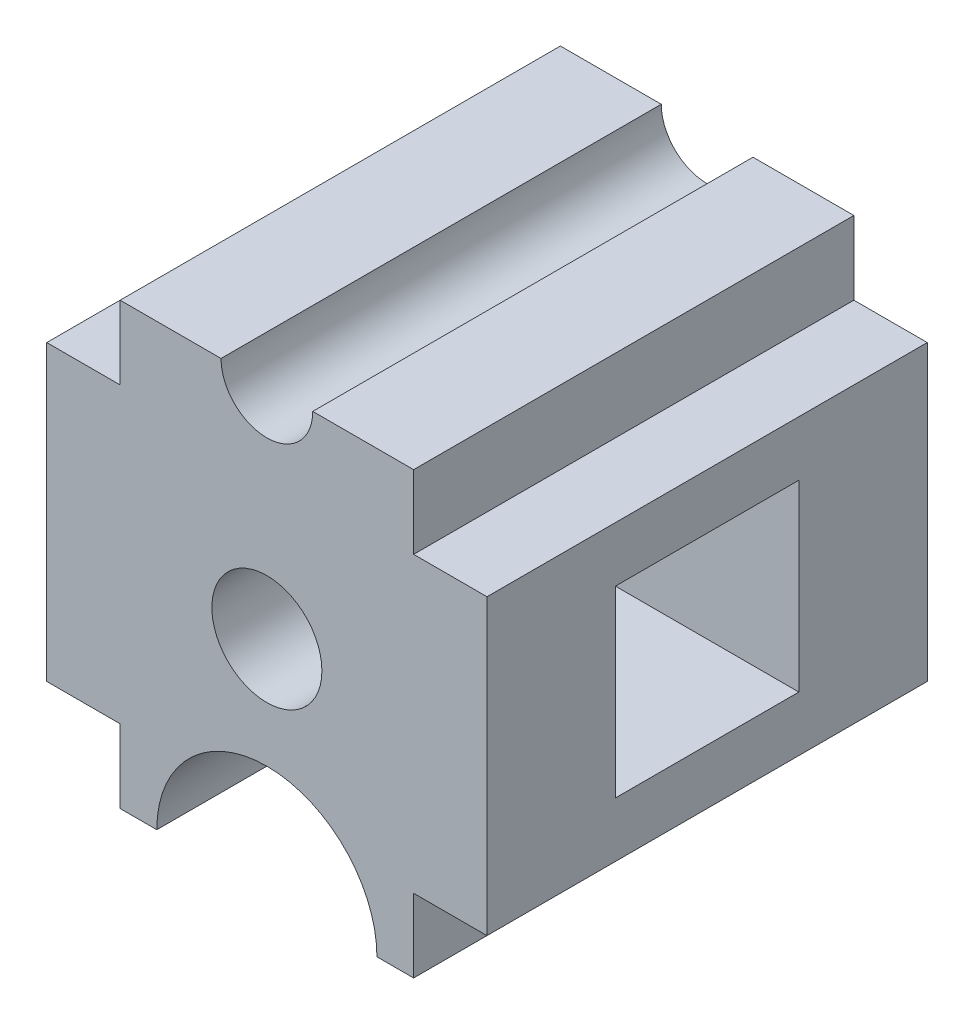
SolidWorks part; units mm, degrees
ref_plane "Front Plane" through (0, 0, 0) normal (0, 0, 1) x (1, 0, 0)
ref_plane "Top Plane" through (0, 0, 0) normal (0, 1, 0) x (1, 0, 0)
ref_plane "Right Plane" through (0, 0, 0) normal (1, 0, 0) x (0, 0, -1)
sketch "Sketch1" plane through (0, 0, 0) normal (0, 0, 1) x (1, 0, 0)
  line L1 (-60, 60) -> (60, 60)
  line L2 (-60, 60) -> (-60, -60)
  line L3 (-60, -60) -> (60, -60)
  line L4 (60, 60) -> (60, -60)
  line L5 (-60, 60) -> (60, -60) construction
  line L6 (-60, -60) -> (60, 60) construction
  point P0 (0, 0)
  dimension "D1" = 120
  dimension "D2" = 120
extrude "Boss-Extrude1" add sketch "Sketch1" along normal blind 120
sketch "Sketch2" plane through (0, 0, 120) normal (0, 0, 1) x (1, 0, 0)
  line L0 (-60, -60) -> (60, -60) construction
  line L1 (60, -60) -> (40, -60)
  line L2 (40, -60) -> (40, -40)
  line L3 (40, -40) -> (60, -40)
  line L4 (60, -60) -> (60, 60) construction
  line L5 (0, -60) -> (0, 60) construction
  line L6 (60, 60) -> (-60, 60) construction
  line L7 (60, -40) -> (60, -60)
  line L8 (-60, -40) -> (-60, -60)
  line L9 (-60, -60) -> (-40, -60)
  line L10 (-40, -60) -> (-40, -40)
  line L11 (-40, -40) -> (-60, -40)
  circle A0 centre (0, -60) radius 30
extrude "Cut-Extrude1" cut sketch "Sketch2" against normal blind 120
sketch "Sketch4" plane through (0, 0, 120) normal (0, 0, 1) x (1, 0, 0)
  circle A0 centre (0, 0) radius 15
  dimension "D1" = 30
extrude "Cut-Extrude2" cut sketch "Sketch4" against normal blind 120
sketch "Sketch5" plane through (0, 0, 120) normal (0, 0, 1) x (1, 0, 0)
  line L1 (-60, 60) -> (-40, 60)
  line L2 (-40, 60) -> (-40, 40)
  line L3 (-40, 40) -> (-60, 40)
  line L4 (-60, 60) -> (-60, -40) construction
  line L5 (-60, 40) -> (-60, 60)
  line L6 (0, 60) -> (0, -30) construction
  line L7 (40, 40) -> (60, 40)
  line L8 (40, 60) -> (40, 40)
  line L9 (60, 60) -> (40, 60)
  line L10 (60, 40) -> (60, 60)
  arc A0 (-12.5, 60) -> (12.5, 60) centre (0, 60) ccw
  arc A1 (30, -60) -> (-30, -60) centre (0, -60) ccw construction
  line M14 (60, -40) -> (60, 60)
  line M15 (60, 60) -> (-60, 60)
  line M16 (-60, 60) -> (-60, -40)
  dimension "D1" = 25
extrude "Cut-Extrude3" cut sketch "Sketch5" against normal blind 120 contours L3 L2 M15 M16 | L6 A0 M15 | L6 A0 M15 | L8 L7 M15 M14
sketch "Sketch6" plane through (60, 0, 0) normal (1, 0, 0) x (0, 0, -1)
  line L0 (0, 0) -> (-120, 0) construction
  line L1 (-85, 25) -> (-35, 25)
  line L2 (-85, 25) -> (-85, -25)
  line L3 (-85, -25) -> (-35, -25)
  line L4 (-35, 25) -> (-35, -25)
  line L5 (-85, 25) -> (-35, -25) construction
  line L6 (-85, -25) -> (-35, 25) construction
  line L7 (0, -40) -> (0, 40) construction
  line L8 (-120, -40) -> (-120, 40) construction
  point P0 (-60, 0)
  point P11 (-60, 0)
  dimension "D1" = 50
  dimension "D2" = 50
extrude "Cut-Extrude4" cut sketch "Sketch6" against normal blind 120
